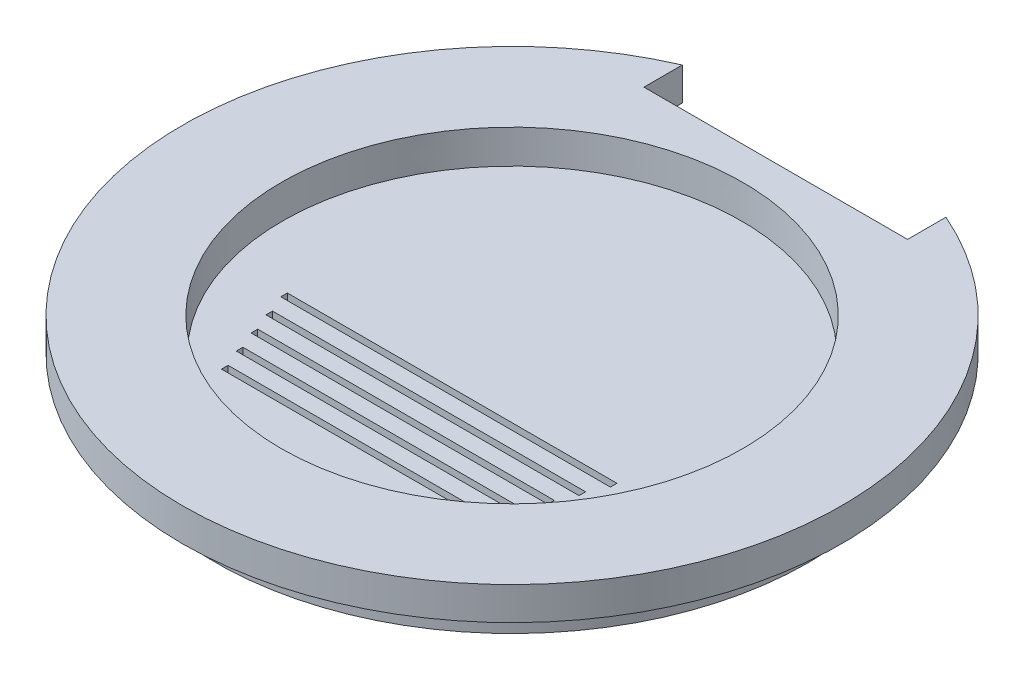
SolidWorks part; units mm, degrees
ref_plane "Front Plane" through (0, 0, 0) normal (0, 0, 1) x (1, 0, 0)
ref_plane "Top Plane" through (0, 0, 0) normal (0, 1, 0) x (1, 0, 0)
ref_plane "Right Plane" through (0, 0, 0) normal (1, 0, 0) x (0, 0, -1)
sketch "Sketch1" plane through (0, 0, 0) normal (0, 1, 0) x (1, 0, 0)
  line L0 (0, 0) -> (0, 97.8591) construction
  line L1 (-120.9894, 70) -> (119.0733, 70) construction
  line L2 (-50, 74.8331) -> (-50, 70)
  line L3 (-50, 70) -> (50, 70)
  line L4 (50, 70) -> (50, 74.8331)
  arc A0 (-50, 74.8331) -> (50, 74.8331) centre (0, 0) ccw
  point P9 (0, 70)
  dimension "D1" = 180
  dimension "D2" = 70
  dimension "D3" = 100
extrude "Boss-Extrude1" add sketch "Sketch1" against normal blind 10 draft 0.5
sketch "Sketch2" plane through (0, 0, 0) normal (0, 1, 0) x (1, 0, 0)
  line L0 (-95.4037, 80) -> (113.7506, 80) construction
  line L1 (-40, 91.6515) -> (-40, 80)
  line L2 (-40, 80) -> (40, 80)
  line L3 (40, 80) -> (40, 91.6515)
  arc A0 (-40, 91.6515) -> (40, 91.6515) centre (0, 0) ccw
  point P9 (0, 80)
  dimension "D1" = 200
  dimension "D2" = 80
  dimension "D3" = 80
extrude "Boss-Extrude2" add sketch "Sketch2" along normal blind 10 contours L2 L3 A0 L1
sketch "Sketch3" plane through (0, 10, 0) normal (0, 1, 0) x (1, 0, 0)
  line L1 (-50, -18.1733) -> (50, -18.1733)
  line L2 (-50, -18.1733) -> (-50, -20.1733)
  line L3 (-50, -20.1733) -> (50, -20.1733)
  line L4 (50, -18.1733) -> (50, -20.1733)
  line L5 (-47.5, -25.1733) -> (47.5, -25.1733)
  line L6 (-47.5, -25.1733) -> (-47.5, -27.1733)
  line L7 (-47.5, -27.1733) -> (47.5, -27.1733)
  line L8 (47.5, -25.1733) -> (47.5, -27.1733)
  line L9 (-45, -32.1733) -> (45, -32.1733)
  line L10 (-45, -32.1733) -> (-45, -34.1733)
  line L11 (-45, -34.1733) -> (45, -34.1733)
  line L12 (45, -32.1733) -> (45, -34.1733)
  line L13 (-42.5, -39.1733) -> (42.5, -39.1733)
  line L14 (-42.5, -39.1733) -> (-42.5, -41.1733)
  line L15 (-42.5, -41.1733) -> (42.5, -41.1733)
  line L16 (42.5, -39.1733) -> (42.5, -41.1733)
  line L17 (-40, -46.1733) -> (40, -46.1733)
  line L18 (-40, -46.1733) -> (-40, -48.1733)
  line L19 (-40, -48.1733) -> (40, -48.1733)
  line L20 (40, -46.1733) -> (40, -48.1733)
  point P20 (0, -18.1733)
  point P21 (0, -25.1733)
  point P22 (0, -32.1733)
  point P23 (0, -39.1733)
  point P24 (0, -46.1733)
  dimension "D1" = 2
  dimension "D2" = 2
  dimension "D3" = 2
  dimension "D4" = 2
  dimension "D5" = 2
  dimension "D6" = 100
  dimension "D7" = 95
  dimension "D8" = 90
  dimension "D9" = 85
  dimension "D10" = 80
  dimension "D11" = 5
  dimension "D12" = 5
  dimension "D13" = 5
  dimension "D14" = 5
extrude "Cut-Extrude1" cut sketch "Sketch3" against normal through all from surface at 0 contours L1 L4 L3 L2 | L7 L8 L5 L6 | L9 L12 L11 L10 | L13 L16 L15 L14 | L19 L20 L17 L18 starting at face at (0, 10, -37.9129)
sketch "Sketch4" plane through (0, 10, 0) normal (0, 1, 0) x (1, 0, 0)
  circle A0 centre (0, 0) radius 70
  line M2 (50, -18.1733) -> (50, -20.1733)
  line M3 (50, -20.1733) -> (-50, -20.1733)
  line M4 (-50, -20.1733) -> (-50, -18.1733)
  line M5 (-50, -18.1733) -> (50, -18.1733)
  line M6 (47.5, -25.1733) -> (47.5, -27.1733)
  line M7 (47.5, -27.1733) -> (-47.5, -27.1733)
  line M8 (-47.5, -27.1733) -> (-47.5, -25.1733)
  line M9 (-47.5, -25.1733) -> (47.5, -25.1733)
  line M10 (45, -32.1733) -> (45, -34.1733)
  line M11 (45, -34.1733) -> (-45, -34.1733)
  line M12 (-45, -34.1733) -> (-45, -32.1733)
  line M13 (-45, -32.1733) -> (45, -32.1733)
  line M14 (42.5, -39.1733) -> (42.5, -41.1733)
  line M15 (42.5, -41.1733) -> (-42.5, -41.1733)
  line M16 (-42.5, -41.1733) -> (-42.5, -39.1733)
  line M17 (-42.5, -39.1733) -> (42.5, -39.1733)
  line M18 (40, -46.1733) -> (40, -48.1733)
  line M19 (40, -48.1733) -> (-40, -48.1733)
  line M20 (-40, -48.1733) -> (-40, -46.1733)
  line M21 (-40, -46.1733) -> (40, -46.1733)
  dimension "D1" = 140
extrude "Cut-Extrude2" cut sketch "Sketch4" against normal blind 10 draft 2 from surface at 0 contours A0 M5 M2 M3 M4 M9 M6 M7 M8 M13 M10 M11 M12 M17 M14 M15 M16 M21 M18 M19 M20 | M2 M5 M4 M3 | M6 M9 M8 M7 | M10 M13 M12 M11 | M14 M17 M16 M15 | M18 M21 M20 M19
